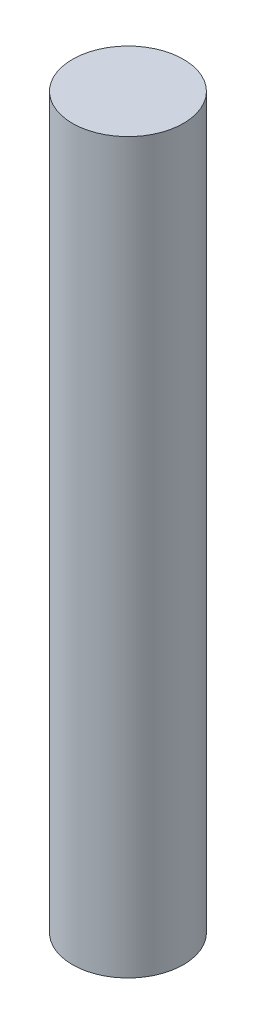
SolidWorks part; units mm, degrees
ref_plane "Front Plane" through (0, 0, 0) normal (0, 0, 1) x (1, 0, 0)
ref_plane "Top Plane" through (0, 0, 0) normal (0, 1, 0) x (1, 0, 0)
ref_plane "Right Plane" through (0, 0, 0) normal (1, 0, 0) x (0, 0, -1)
sketch "Sketch1" plane through (0, 0, 0) normal (0, 1, 0) x (1, 0, 0)
  circle A0 centre (0, 0) radius 27.5
  dimension "D1" = 55
extrude "Boss-Extrude1" add sketch "Sketch1" against normal blind 361
